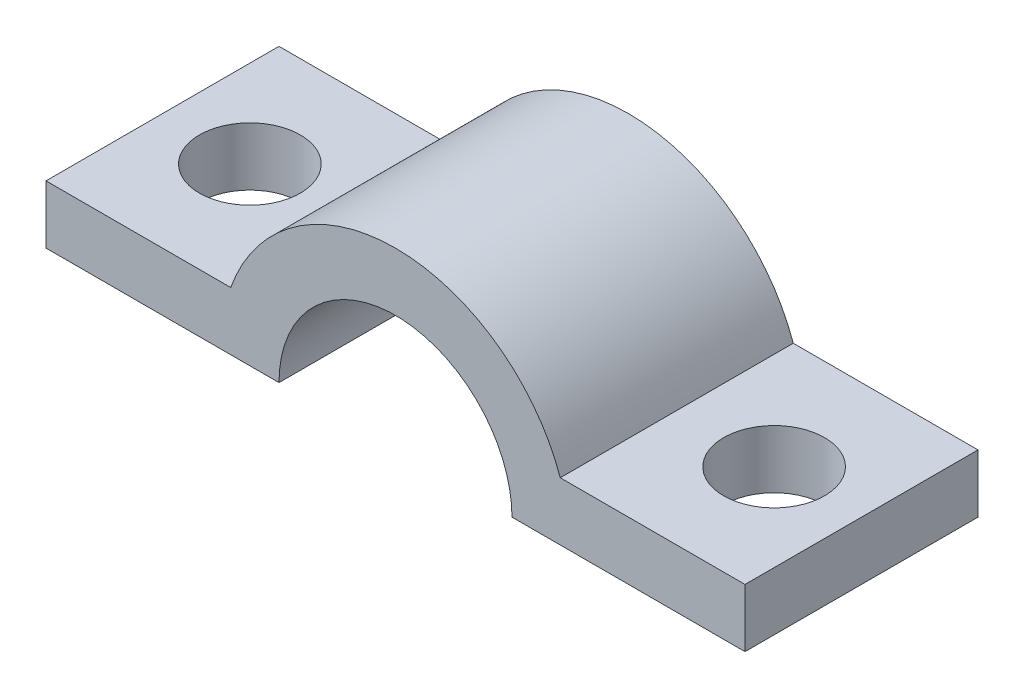
SolidWorks part; units mm, degrees
ref_plane "Front Plane" through (0, 0, 0) normal (0, 0, 1) x (1, 0, 0)
ref_plane "Top Plane" through (0, 0, 0) normal (0, 1, 0) x (1, 0, 0)
ref_plane "Right Plane" through (0, 0, 0) normal (1, 0, 0) x (0, 0, -1)
sketch "Sketch1" plane through (0, 0, 0) normal (0, 0, 1) x (1, 0, 0)
  line L0 (25.4, 0) -> (38.1, 0)
  line L1 (0, 0) -> (12.7, 0)
  line L2 (0, 0) -> (0, 3.175)
  line L3 (0, 3.175) -> (10.0697, 3.175)
  line L4 (38.1, 0) -> (38.1, 3.175)
  line L5 (28.0303, 3.175) -> (38.1, 3.175)
  arc A0 (28.0303, 3.175) -> (10.0697, 3.175) centre (19.05, 0) ccw
  arc A1 (12.7, 0) -> (25.4, 0) centre (19.05, 0) cw
  dimension "D1" = 9.525
  dimension "D2" = 6.35
  dimension "D6" = 12.7
  dimension "D3" = 12.7
  dimension "D4" = 12.7
  dimension "D5" = 3.175
extrude "Boss-Extrude1" add sketch "Sketch1" along normal blind 12.7
sketch "Sketch2" plane through (0, 3.175, 0) normal (0, 1, 0) x (1, 0, 0)
  line L0 (10.0697, 0) -> (0, 0) construction
  line L1 (0, -12.7) -> (0, 0) construction
  line L2 (38.1, -12.7) -> (38.1, 0) construction
  point P0 (4.7625, -6.35)
  point P1 (33.3375, -6.35)
  point P8 (0, 0)
  dimension "D1" = 6.35
  dimension "D2" = 4.7625
  dimension "D3" = 4.7625
hole_wizard "M5 Clearance Hole2" positions "Sketch7" profile "Sketch8" hole size "M5" standard "ANSI Metric" end condition through all
sketch "Sketch7" plane through (0, 3.175, 0) normal (0, 1, 0) x (1, 0, 0)
  point P0 (4.7625, -6.35)
  point P3 (33.3375, -6.35)
sketch "Sketch8" plane through (4.7625, 3.175, 6.35) normal (1, 0, 0) x (0, 0, 1)
  line L0 (0, 0) -> (0, 3.175)
  line L1 (0, 3.175) -> (2.75, 3.175)
  line L2 (2.75, 3.175) -> (2.75, 0)
  line L5 (2.75, 0) -> (0, 0)
  line L11 (0, -6.35) -> (0, 107.95) construction
  dimension "Thru Hole Dia." = 5.5
  dimension "Thru Hole Depth" = 3.175
